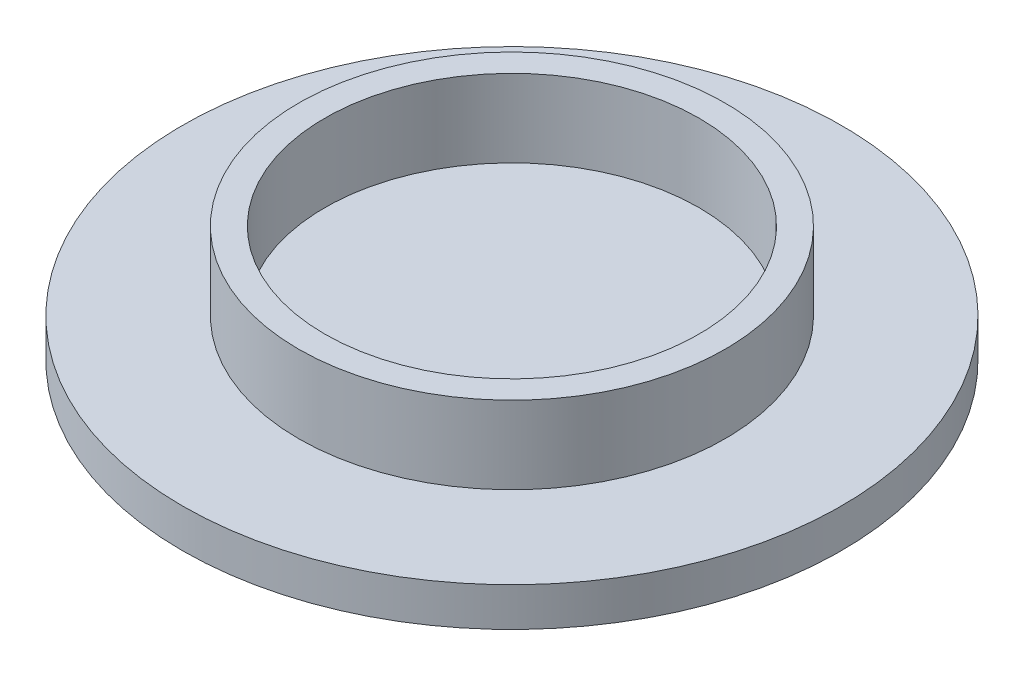
SolidWorks part; units mm, degrees
material "2024 Alloy"
ref_plane "Front Plane" through (0, 0, 0) normal (0, 0, 1) x (1, 0, 0)
ref_plane "Top Plane" through (0, 0, 0) normal (0, 1, 0) x (1, 0, 0)
ref_plane "Right Plane" through (0, 0, 0) normal (1, 0, 0) x (0, 0, -1)
sketch "Sketch1" plane through (0, 0, 0) normal (0, 1, 0) x (1, 0, 0)
  circle A0 centre (0, 0) radius 9.652
  circle A1 centre (0, 0) radius 11
  circle A2 centre (0, 0) radius 17
  dimension "D1" = 19.304
  dimension "D2" = 22
  dimension "D3" = 34
extrude "Boss-Extrude1" add sketch "Sketch1" against normal blind 1 contours A2
sketch "Sketch2" plane through (0, 0, 0) normal (0, 1, 0) x (1, 0, 0)
  circle A0 centre (0, 0) radius 9.652
  circle A1 centre (0, 0) radius 11
  circle A2 centre (0, 0) radius 11 construction
  circle A3 centre (0, 0) radius 9.652 construction
extrude "Boss-Extrude2" add sketch "Sketch2" along normal blind 4
mirror "Mirror1" about plane through (0, -1, 0) normal (0, 1, 0) of "Boss-Extrude2", "Boss-Extrude1"
